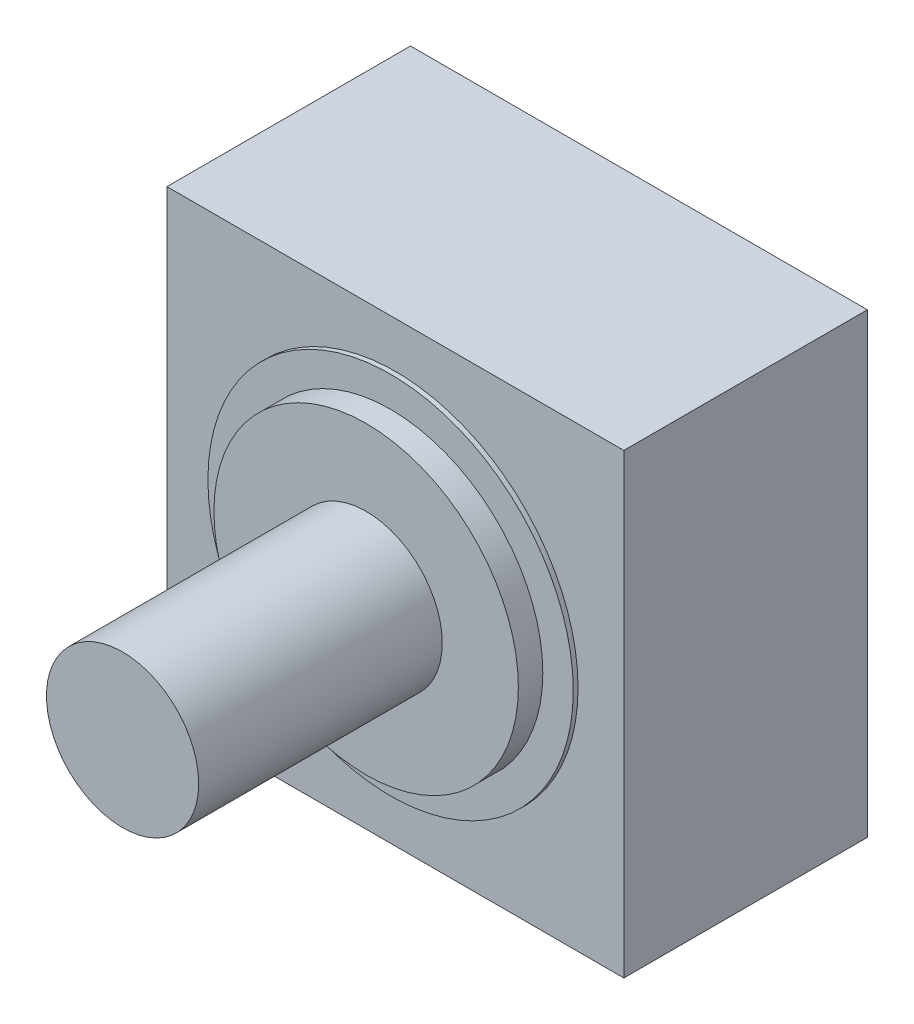
SolidWorks part; units mm, degrees
ref_plane "Front Plane" through (0, 0, 0) normal (0, 0, 1) x (1, 0, 0)
ref_plane "Top Plane" through (0, 0, 0) normal (0, 1, 0) x (1, 0, 0)
ref_plane "Right Plane" through (0, 0, 0) normal (1, 0, 0) x (0, 0, -1)
sketch "Sketch1" plane through (0, 0, 0) normal (0, 0, 1) x (1, 0, 0)
  line L1 (0, 0) -> (9.53, 0)
  line L2 (0, 0) -> (0, 9.53)
  line L3 (0, 9.53) -> (9.53, 9.53)
  line L4 (9.53, 0) -> (9.53, 9.53)
  dimension "D1" = 9.53
  dimension "D2" = 9.53
extrude "Boss-Extrude1" add sketch "Sketch1" along normal blind 5.08
sketch "Sketch2" plane through (0, 0, 5.08) normal (0, 0, 1) x (1, 0, 0)
  line L0 (0, 9.53) -> (9.53, 0) construction
  line L1 (0, 0) -> (9.53, 9.53) construction
  circle A0 centre (4.765, 4.765) radius 3.81
  dimension "D1" = 7.62
extrude "Boss-Extrude2" add sketch "Sketch2" along normal blind 0.1
sketch "Sketch3" plane through (0, 0, 5.18) normal (0, 0, 1) x (1, 0, 0)
  circle A0 centre (4.765, 4.765) radius 3.175
  dimension "D1" = 6.35
extrude "Boss-Extrude3" add sketch "Sketch3" along normal blind 0.51
sketch "Sketch4" plane through (0, 0, 5.69) normal (0, 0, 1) x (1, 0, 0)
  circle A0 centre (4.765, 4.765) radius 1.5875
  dimension "D1" = 3.175
extrude "Boss-Extrude4" add sketch "Sketch4" along normal blind 5.08
